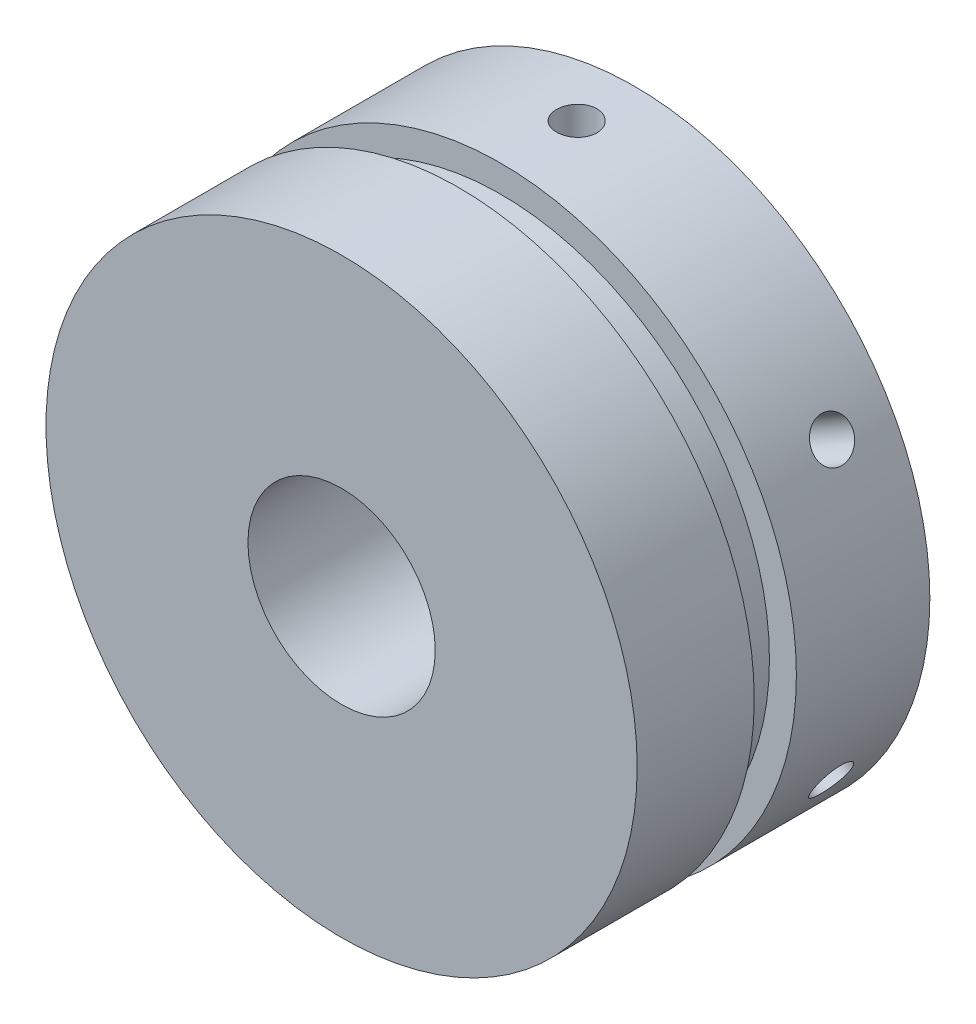
SolidWorks part; units mm, degrees
material "AISI 304"
ref_plane "Front Plane" through (0, 0, 0) normal (0, 0, 1) x (1, 0, 0)
ref_plane "Top Plane" through (0, 0, 0) normal (0, 1, 0) x (1, 0, 0)
ref_plane "Right Plane" through (0, 0, 0) normal (1, 0, 0) x (0, 0, -1)
sketch "Sketch2" plane through (0, 0, 0) normal (0, 0, 1) x (1, 0, 0)
  circle A0 centre (0, 0) radius 25.25
  dimension "D1" = 50.5
extrude "Boss-Extrude1" add sketch "Sketch2" along normal blind 25
sketch "Sketch6" plane through (0, 0, 0) normal (1, 0, 0) x (0, 0, -1)
  line L0 (-25, 0) -> (-25, 8)
  line L1 (0, 0) -> (0, 4.06)
  line L3 (-25, 8) -> (-13.59, 8)
  line L4 (0, 0) -> (-25, 0) construction
  line L5 (-13.59, 8) -> (-9.7997, 1.435)
  line L6 (-9.7997, 1.435) -> (0, 4.06)
  line L7 (0, -25.25) -> (0, 25.25) construction
  line L8 (-25, 25.25) -> (-25, -25.25) construction
  line L9 (-25, 0) -> (0, 0)
  dimension "D2" = 4.06
  dimension "D3" = 11.41
  dimension "D5" = 60
  dimension "D1" = 8
  dimension "D4" = 1.435
revolve "Cut-Revolve2" cut sketch "Sketch6" angle 360 about L4
sketch "Sketch8" plane through (0, 0, 0) normal (1, 0, 0) x (0, 0, -1)
  line L0 (-15, 25.25) -> (-15, 22.95)
  line L3 (-25, 0) -> (0, 0) construction
  line L5 (0, 25.25) -> (-25, 25.25) construction
  line L6 (-15, 22.95) -> (-11.4, 22.95)
  line L7 (-11.4, 22.95) -> (-11.4, 25.25)
  line L8 (-25, 25.25) -> (-25, -25.25) construction
  line L9 (-15, 25.25) -> (-11.4, 25.25)
  dimension "D1" = 10
  dimension "D2" = 3.6
  dimension "D3" = 2.3
revolve "Cut-Revolve3" cut sketch "Sketch8" angle 360 about L3
ref_plane "Plane1" through (0, 25.25, 0) normal (0, 1, 0) x (1, 0, 0)
hole_wizard "#8-32 Tapped Hole1" positions "3DSketch1" profile "Sketch9" tap size "#8-32" standard "ANSI Inch"
sketch3d "3DSketch1"
  line L7 (0, 8, 25) -> (0, 8, 13.59) construction
  line L8 (0, 8, 25) -> (0, 25.25, 25)
  line L12 (0, 0, 0) -> (0.0792, 25.2499, 0)
  line L14 (0.0792, 25.2499, 0) -> (0.0792, 25.2499, 5)
  circle A5 centre (0, 0, 25) radius 8 construction
  circle A6 centre (0, 0, 25) radius 25.25 construction
  circle A7 centre (0, 0, 0) radius 25.25 construction
  point P0 (0.0792, 25.2499, 5)
  point P38 (0, 0, 17)
  point P42 (0, 0, 50.25)
  point P62 (0, 0, 25.25)
  dimension "D2" = 5
cosmetic thread "Hole Thread7" parameters "D1"=8.33, "D2"=4.1656
sketch "Sketch9" plane through (0.0792, 25.2499, 5) normal (0, 0, 1) x (-1, 0.0031, 0)
  line L0 (0, 0) -> (0, 11.0378)
  line L1 (0, 11.0378) -> (1.7272, 10)
  line L2 (1.7272, 10) -> (1.7272, 0)
  line L5 (1.7272, 0) -> (0, 0)
  line L10 (0, 11.0378) -> (-1.7272, 10) construction
  line L11 (0, -6.35) -> (0, 107.95) construction
  dimension "Tap Drill Dia." = 3.4544
  dimension "Tap Drill Depth" = 10
  dimension "Drill Angle" = 118
pattern_circular "CirPattern1" count 6 over 360 about axis through (0, 0, 25) along (0, 0, -1) of "#8-32 Tapped Hole1"
cosmetic thread "Hole Thread8" parameters "D1"=8.33, "D2"=4.1656
cosmetic thread "Hole Thread9" parameters "D1"=8.33, "D2"=4.1656
cosmetic thread "Hole Thread10" parameters "D1"=8.33, "D2"=4.1656
cosmetic thread "Hole Thread11" parameters "D1"=8.33, "D2"=4.1656
cosmetic thread "Hole Thread12" parameters "D1"=8.33, "D2"=4.1656
